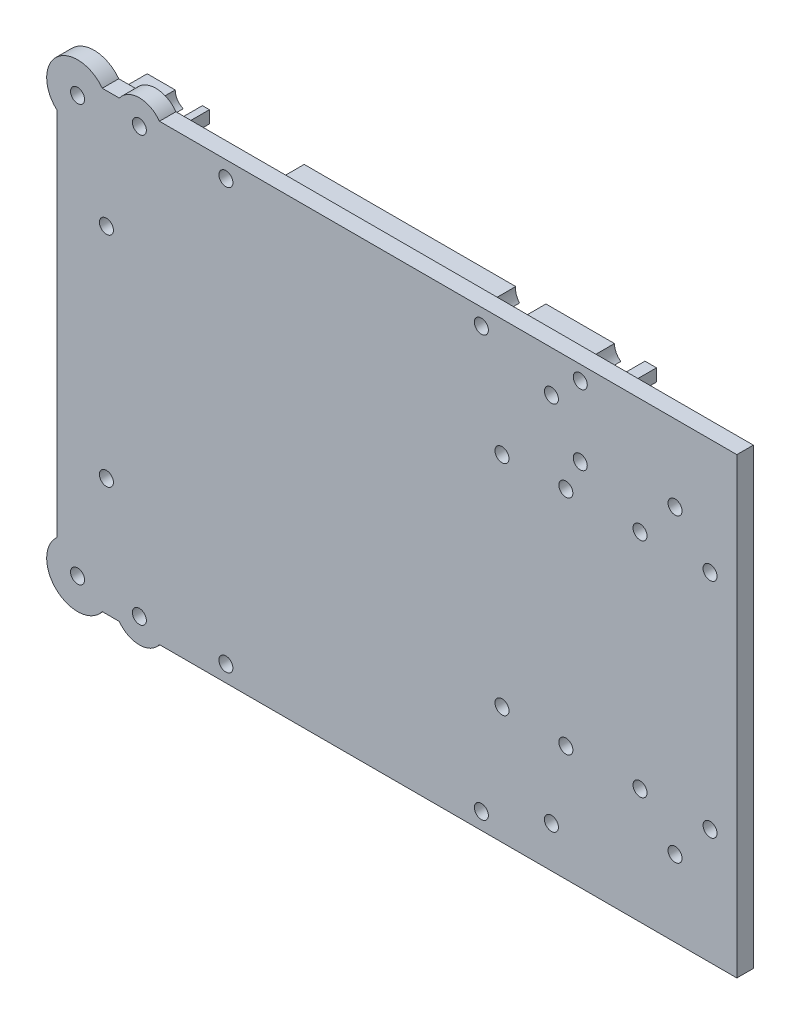
SolidWorks part; units mm, degrees
other "Platform Segment 1"
ref_plane "Front Plane" through (0, 0, 0) normal (0, 0, 1) x (1, 0, 0)
ref_plane "Top Plane" through (0, 0, 0) normal (0, 1, 0) x (1, 0, 0)
ref_plane "Right Plane" through (0, 0, 0) normal (1, 0, 0) x (0, 0, -1)
sketch3d "Main Profile Sketch datum points"
  point P0 (0, 0, 48.5)
  point P1 (10, 0, 48.5)
  point P2 (0, 10, 48.5)
ref_plane "Main Profile Sketch plane" through (0, 0, 48.5) normal (0, 0, 1) x (1, 0, 0)
sketch "Main Profile Sketch" plane through (0, 0, 48.5) normal (0, 0, 1) x (1, 0, 0)
  line L0 (-110, 55) -> (-110, -55)
  line L1 (-250.1266, -55) -> (-110, -55)
  line L2 (-264, -55) -> (-259.8734, -55)
  line L3 (-275, 44.9098) -> (-275, -44.9098)
  line L4 (-264, 55) -> (-259.8734, 55)
  line L5 (-250.1266, 55) -> (-110, 55)
  arc A0 (-259.8734, -55) -> (-250.1266, -55) centre (-255, -51.5) ccw
  arc A1 (-275, -44.9098) -> (-264, -55) centre (-270, -50.5) ccw
  arc A2 (-264, 55) -> (-275, 44.9098) centre (-270, 50.5) ccw
  arc A3 (-250.1266, 55) -> (-259.8734, 55) centre (-255, 51.5) ccw
  circle A4 centre (-270, -50.5) radius 1.7
  circle A5 centre (-255, -51.5) radius 1.7
  circle A6 centre (-234, -51) radius 1.7
  circle A7 centre (-263, -26.5) radius 1.7
  circle A8 centre (-172, -51) radius 1.7
  circle A9 centre (-155, -45) radius 1.7
  circle A10 centre (-125, -36.5) radius 1.7
  circle A11 centre (-167, -26.5) radius 1.7
  circle A12 centre (-151.5, -27) radius 1.7
  circle A13 centre (-133.5, -27) radius 1.7
  circle A14 centre (-116.5, -27) radius 1.7
  circle A15 centre (-263, 26.5) radius 1.7
  circle A16 centre (-270, 50.5) radius 1.7
  circle A17 centre (-255, 51.5) radius 1.7
  circle A18 centre (-234, 51) radius 1.7
  circle A19 centre (-167, 26.5) radius 1.7
  circle A20 centre (-151.5, 27) radius 1.7
  circle A21 centre (-133.5, 27) radius 1.7
  circle A22 centre (-116.5, 27) radius 1.7
  circle A23 centre (-155, 45) radius 1.7
  circle A24 centre (-172, 51) radius 1.7
  circle A25 centre (-148, 34.5) radius 1.7
  circle A26 centre (-125, 36.5) radius 1.7
  circle A27 centre (-148, 51.5) radius 1.7
extrude "Main Extrusion" add sketch "Main Profile Sketch" against normal blind 4 separate body
sketch3d "Detail Profile 2 Sketch datum points"
  point P0 (0, 0, 44.5)
  point P1 (10, 0, 44.5)
  point P2 (0, 10, 44.5)
ref_plane "Detail Profile 2 Sketch plane" through (0, 0, 44.5) normal (0, 0, 1) x (1, 0, 0)
sketch "Detail Profile 2 Sketch" plane through (0, 0, 44.5) normal (0, 0, 1) x (1, 0, 0)
  line L0 (-265.4174, -48.5) -> (-256.3748, -48.5)
  line L1 (-265.101, -51.5) -> (-258.3, -51.5)
  line L2 (-253.6252, -48.5) -> (-250, -48.5)
  line L3 (-250, -48.5) -> (-250, -51.5)
  line L4 (-251.7, -51.5) -> (-250, -51.5)
  line L5 (-227, -51.5) -> (-175.6661, -51.5)
  line L6 (-227, -48.5) -> (-227, -51.5)
  line L7 (-227, -48.5) -> (-174.7276, -48.5)
  line L8 (-141.5, -48.5) -> (-141.5, -51.5)
  line L9 (-168.3339, -51.5) -> (-141.5, -51.5)
  line L10 (-169.2724, -48.5) -> (-141.5, -48.5)
  line L11 (-265.101, 51.5) -> (-258.3, 51.5)
  line L12 (-265.4174, 48.5) -> (-256.3748, 48.5)
  line L13 (-251.7, 51.5) -> (-250, 51.5)
  line L14 (-250, 51.5) -> (-250, 48.5)
  line L15 (-253.6252, 48.5) -> (-250, 48.5)
  line L16 (-227, 48.5) -> (-174.7276, 48.5)
  line L17 (-227, 51.5) -> (-227, 48.5)
  line L18 (-227, 51.5) -> (-175.6661, 51.5)
  line L19 (-169.2724, 48.5) -> (-150.1656, 48.5)
  line L20 (-168.3339, 51.5) -> (-151.7, 51.5)
  line L21 (-141.5, 51.5) -> (-141.5, 48.5)
  line L22 (-145.8344, 48.5) -> (-141.5, 48.5)
  line L23 (-144.3, 51.5) -> (-141.5, 51.5)
  arc A0 (-265.101, -51.5) -> (-265.4174, -48.5) centre (-270, -50.5) ccw
  arc A1 (-256.3748, -48.5) -> (-258.3, -51.5) centre (-255, -51.5) ccw
  arc A2 (-251.7, -51.5) -> (-253.6252, -48.5) centre (-255, -51.5) ccw
  arc A3 (-174.7276, -48.5) -> (-175.6661, -51.5) centre (-172, -51) ccw
  arc A4 (-168.3339, -51.5) -> (-169.2724, -48.5) centre (-172, -51) ccw
  arc A5 (-265.4174, 48.5) -> (-265.101, 51.5) centre (-270, 50.5) ccw
  arc A6 (-258.3, 51.5) -> (-256.3748, 48.5) centre (-255, 51.5) ccw
  arc A7 (-253.6252, 48.5) -> (-251.7, 51.5) centre (-255, 51.5) ccw
  arc A8 (-175.6661, 51.5) -> (-174.7276, 48.5) centre (-172, 51) ccw
  arc A9 (-151.7, 51.5) -> (-150.1656, 48.5) centre (-148, 51.5) ccw
  arc A10 (-169.2724, 48.5) -> (-168.3339, 51.5) centre (-172, 51) ccw
  arc A11 (-145.8344, 48.5) -> (-144.3, 51.5) centre (-148, 51.5) ccw
extrude "Detail Extrusion 2" add sketch "Detail Profile 2 Sketch" against normal blind 8
